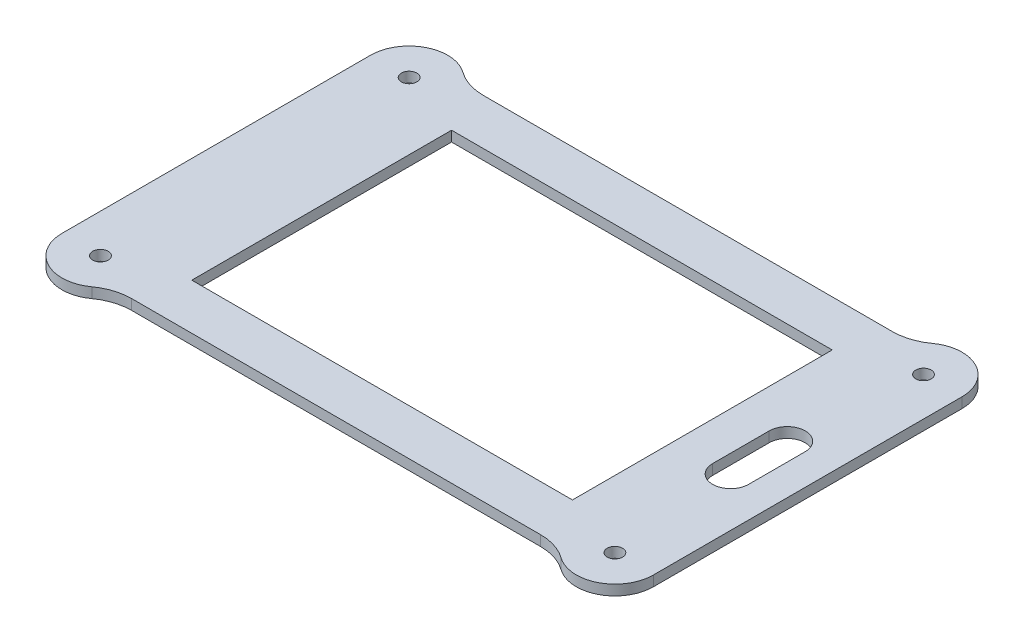
SolidWorks part; units mm, degrees
material "ABS"
ref_plane "Front Plane" through (0, 0, 0) normal (0, 0, 1) x (1, 0, 0)
ref_plane "Top Plane" through (0, 0, 0) normal (0, 1, 0) x (1, 0, 0)
ref_plane "Right Plane" through (0, 0, 0) normal (1, 0, 0) x (0, 0, -1)
sketch "Sketch2" plane through (0, 0, 0) normal (0, 1, 0) x (1, 0, 0)
  line L0 (-50, 30) -> (-50, -30) construction
  line L1 (-37, 25.25) -> (37, 25.25)
  line L2 (-37, 25.25) -> (-37, -25.25)
  line L3 (-37, -25.25) -> (37, -25.25)
  line L4 (37, 25.25) -> (37, -25.25)
  line L5 (-50, -30) -> (50, -30) construction
  line L6 (50, -30) -> (50, 30) construction
  line L7 (-50, 0) -> (0, 0) construction
  line L8 (0, 0) -> (50, 0) construction
  line L9 (0, 25.25) -> (0, 0) construction
  line L10 (0, 0) -> (0, -25.25) construction
  line L11 (0, 25.25) -> (0, 34.1947) construction
  line L12 (-43.7827, 34.1947) -> (43.7827, 34.1947)
  line L13 (-50, 30) -> (50, 30) construction
  line L14 (-54.1947, 23.7827) -> (-54.1947, -23.7827)
  line L15 (-43.7827, -34.1947) -> (43.7827, -34.1947)
  line L16 (54.1947, 23.7827) -> (54.1947, -23.7827)
  line L17 (0, -25.25) -> (0, -34.1947) construction
  line L18 (48, 5.5) -> (48, -5.5) construction
  line L19 (54.1947, -30) -> (50, -30) construction
  line L20 (50, -30) -> (50, -34.1947) construction
  line L21 (51.5, 5.5) -> (51.5, -5.5)
  line L22 (44.5, 5.5) -> (44.5, -5.5)
  circle A0 centre (-50, -30) radius 1.5
  circle A1 centre (50, -30) radius 1.5
  circle A2 centre (-50, 30) radius 1.5
  circle A3 centre (50, 30) radius 1.5
  arc A4 (-43.7827, 34.1947) -> (-54.1947, 23.7827) centre (-50, 30) ccw
  arc A5 (-54.1947, -23.7827) -> (-43.7827, -34.1947) centre (-50, -30) ccw
  arc A6 (43.7827, -34.1947) -> (54.1947, -23.7827) centre (50, -30) ccw
  arc A7 (54.1947, 23.7827) -> (43.7827, 34.1947) centre (50, 30) ccw
  arc A8 (51.5, 5.5) -> (44.5, 5.5) centre (48, 5.5) ccw
  arc A9 (44.5, -5.5) -> (51.5, -5.5) centre (48, -5.5) ccw
  arc A12 (50.5, 5.5) -> (45.5, 5.5) centre (48, 5.5) ccw construction
  arc A13 (46.7119, -7.6426) -> (49.2881, -7.6426) centre (48, -5.5) ccw construction
  point P32 (48, 0)
  dimension "D9" = 3
  dimension "D2" = 15
  dimension "D3" = 4.1947
  dimension "D4" = 1
  dimension "D1" = 60
  dimension "D5" = 50.5
  dimension "D6" = 74
  dimension "D8" = 100
extrude "Boss-Extrude1" add sketch "Sketch2" along normal blind 2
sketch "Sketch4" plane through (0, 2, 0) normal (0, 1, 0) x (1, 0, 0)
  line L0 (-29.714, 0) -> (0, 0) construction
  line L1 (57.5, 30) -> (57.5, -30)
  line L2 (54.1947, 23.7827) -> (54.1947, -23.7827) construction
  line L3 (57.5, 30) -> (51.5, 30)
  line L4 (51.5, 30) -> (51.5, -30)
  line L5 (51.5, -30) -> (57.5, -30)
  line L7 (51.5, -5.5) -> (51.5, 5.5) construction
  arc A0 (54.1947, 23.7827) -> (54.1947, -23.7827) centre (-29.714, 0) cw construction
  arc A1 (54.1947, 23.7827) -> (43.7827, 34.1947) centre (50, 30) ccw construction
  arc A2 (43.7827, -34.1947) -> (54.1947, -23.7827) centre (50, -30) ccw construction
extrude "Boss-Extrude3" add sketch "Sketch4" against normal through all
mirror "Mirror1" about plane through (0, 0, 0) normal (1, 0, 0) of "Boss-Extrude3"
fillet "Fillet1" radius 10 4 edges at (-43.7827, 1, -34.1947) (-43.7827, 1, 34.1947) (43.7827, 1, -34.1947) (43.7827, 1, 34.1947)
